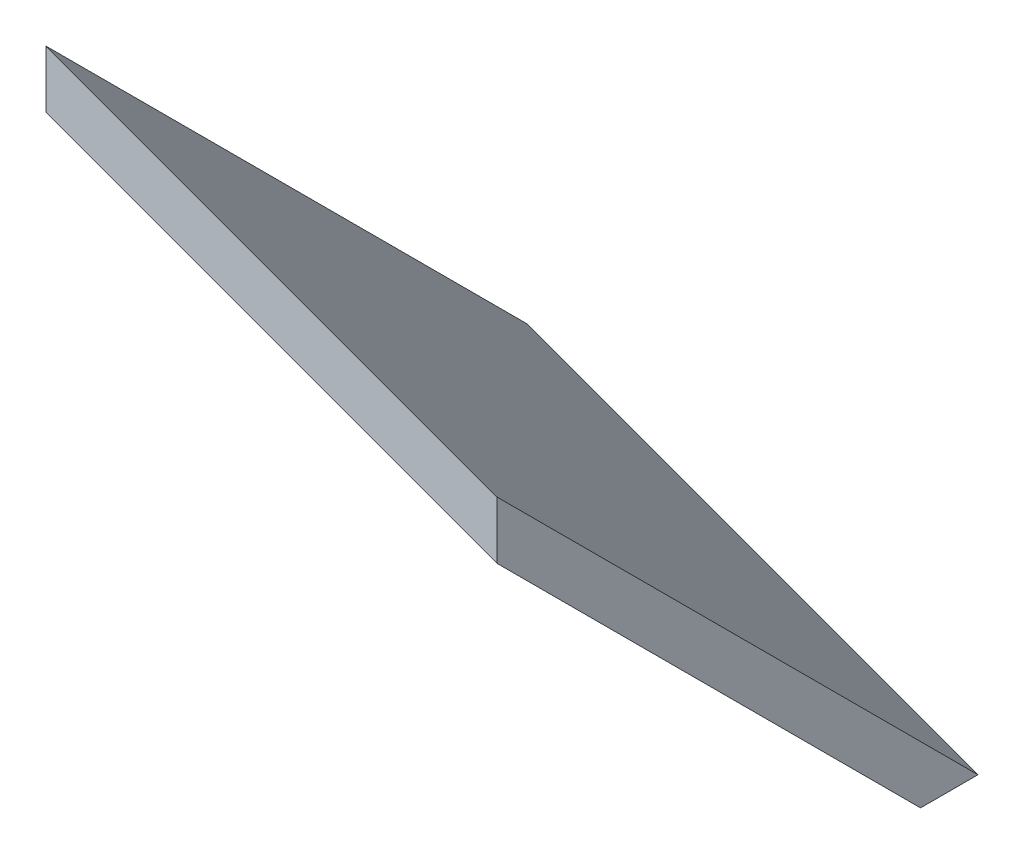
SolidWorks part; units mm, degrees
ref_plane "Front Plane" through (0, 0, 0) normal (0, 0, 1) x (1, 0, 0)
ref_plane "Top Plane" through (0, 0, 0) normal (0, 1, 0) x (1, 0, 0)
ref_plane "Right Plane" through (0, 0, 0) normal (1, 0, 0) x (0, 0, -1)
sketch "Sketch1" plane through (0, 0, 0) normal (1, 0, 0) x (0, 0, -1)
  line L0 (0, 114.3) -> (114.3, 0)
  line L1 (114.3, 0) -> (129.8, 0)
  line L2 (129.8, 0) -> (0, 129.8)
  line L3 (0, 129.8) -> (0, 114.3)
  line L4 (0, 0) -> (0, 114.3) construction
  dimension "D1" = 114.3
  dimension "D2" = 114.3
  dimension "D3" = 15.5
sketch "Sketch2" plane through (0, 0, 0) normal (0, 1, 0) x (1, 0, 0)
  line L0 (0, 129.8) -> (-166.1392, 174.3169)
  line L1 (0, 129.8) -> (-77.6709, 129.8) construction
  dimension "D1" = 15
  dimension "D2" = 172
sweep "Sweep1" add profiles "Sketch1" path "Sketch2"
